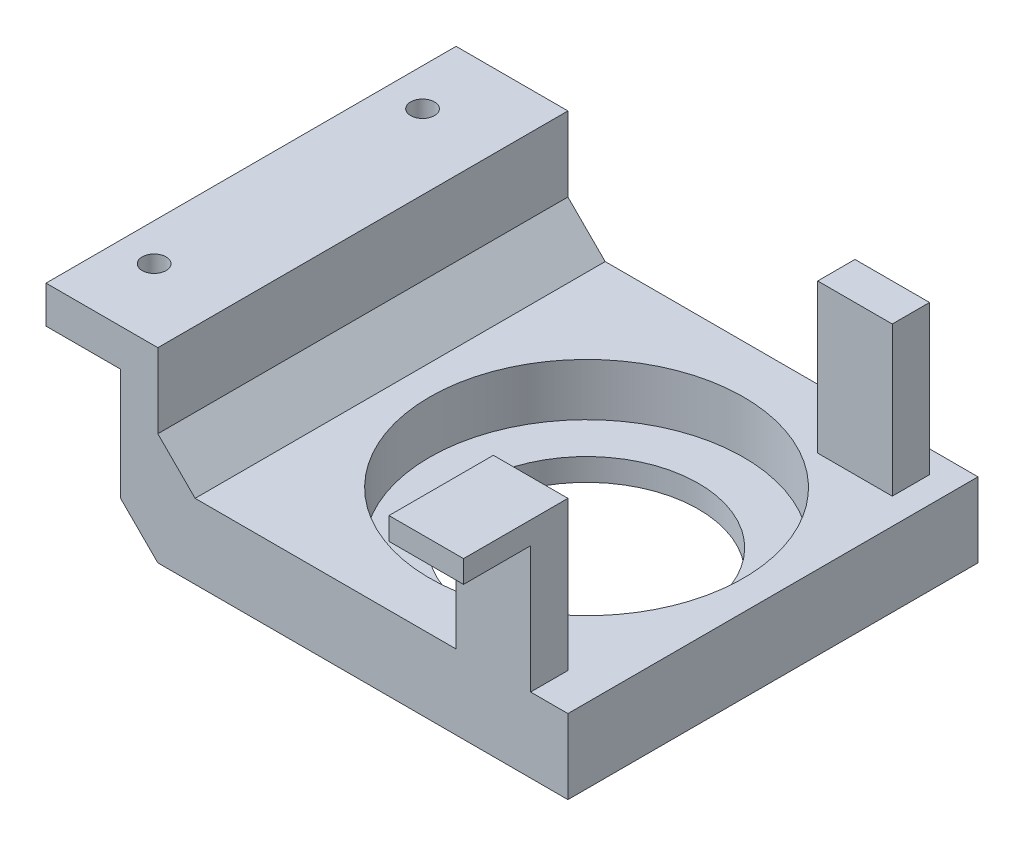
SolidWorks part; units mm, degrees
ref_plane "Alzado" through (0, 0, 0) normal (0, 0, 1) x (1, 0, 0)
ref_plane "Planta" through (0, 0, 0) normal (0, 1, 0) x (1, 0, 0)
ref_plane "Vista lateral" through (0, 0, 0) normal (1, 0, 0) x (0, 0, -1)
sketch "Croquis4" plane through (0, 0, 0) normal (0, 0, 1) x (1, 0, 0)
  line L0 (-31.4286, 5.7619) -> (-31.4286, 14.7619)
  line L5 (-26.4286, 4.7619) -> (28.5714, 4.7619)
  line L6 (-31.4286, 5.7619) -> (-31.4286, -5.2381)
  line L7 (-31.4286, -5.2381) -> (28.5714, -5.2381)
  line L8 (28.5714, 4.7619) -> (28.5714, -5.2381)
  line L9 (-31.4286, 5.7619) -> (28.5714, -5.2381) construction
  line L10 (-31.4286, -5.2381) -> (28.5714, 4.7619) construction
  line L11 (-31.4286, 14.7619) -> (-41.4286, 14.7619)
  line L12 (-41.4286, 14.7619) -> (-41.4286, 19.7619)
  line L13 (-41.4286, 19.7619) -> (-26.4286, 19.7619)
  line L14 (-26.4286, 19.7619) -> (-26.4286, 4.7619)
  point P0 (0, 0)
  dimension "D1" = 11
  dimension "D2" = 60
  dimension "D3" = 5
  dimension "D4" = 5
  dimension "D5" = 10
  dimension "D6" = 10
  dimension "D7" = 15
extrude "Saliente-Extruir2" add sketch "Croquis4" along normal blind 55
sketch "Croquis6" plane through (0, 4.7619, 0) normal (0, 1, 0) x (1, 0, 0)
  line L1 (28.5714, -55) -> (28.5714, 0) construction
  line L2 (28.5714, -27.5) -> (-26.4286, -27.5) construction
  line L3 (-26.4286, -55) -> (-26.4286, 0) construction
  circle A0 centre (3.5714, -27.5) radius 21.05
  dimension "D1" = 42.1
  dimension "D3" = 25
extrude "Cortar-Extruir1" cut sketch "Croquis6" against normal blind 7
sketch "Croquis8" plane through (0, -2.2381, 0) normal (0, 1, 0) x (1, 0, 0)
  circle A0 centre (3.5714, -27.5) radius 15
  dimension "D1" = 30
extrude "Cortar-Extruir2" cut sketch "Croquis8" against normal through all both and the other way through all
sketch "Croquis9" plane through (0, 14.7619, 0) normal (0, -1, 0) x (1, 0, 0)
  line L0 (-41.4286, 27.5) -> (-31.4286, 27.5) construction
  line L1 (-41.4286, 55) -> (-41.4286, 0) construction
  line L2 (-31.4286, 55) -> (-31.4286, 0) construction
  line L3 (-36.4286, 27.5) -> (-36.4286, 61.1151) construction
  circle A0 centre (-36.4286, 45.5) radius 1.6
  circle A2 centre (-36.4286, 9.5) radius 1.6
  dimension "D1" = 18
  dimension "D2" = 3.2
extrude "Cortar-Extruir3" cut sketch "Croquis9" against normal through all both and the other way through all
chamfer "Chaflán1" distance 5 angle 45 2 edges at (-26.4286, 4.7619, 27.5) (-31.4286, -5.2381, 27.5)
sketch "Croquis11" plane through (0, 4.7619, 0) normal (0, 1, 0) x (1, 0, 0)
  line L1 (28.5714, -55) -> (28.5714, 0) construction
  line L6 (28.5714, -27.5) -> (-21.4286, -27.5) construction
  line L7 (-21.4286, 0) -> (-21.4286, -55) construction
  line L12 (23.5714, -55) -> (23.5714, -50)
  line L13 (28.5714, -55) -> (-21.4286, -55) construction
  line L14 (23.5714, -50) -> (13.5714, -50)
  line L15 (13.5714, -50) -> (13.5714, -55)
  line L16 (13.5714, -55) -> (23.5714, -55)
  dimension "D1" = 10
  dimension "D2" = 5
  dimension "D3" = 5
extrude "Saliente-Extruir3" add sketch "Croquis11" along normal blind 20
sketch "Croquis12" plane through (0, 0, 55) normal (0, 0, 1) x (1, 0, 0)
  line L7 (13.5714, 24.7619) -> (13.5714, 21.7619)
  line L8 (13.5714, 24.7619) -> (23.5714, 24.7619) construction
  line L9 (13.5714, 24.7619) -> (13.5714, 4.7619) construction
  line L10 (13.5714, 21.7619) -> (23.5714, 21.7619)
  line L11 (23.5714, 24.7619) -> (23.5714, 4.7619) construction
  line L12 (23.5714, 21.7619) -> (23.5714, 24.7619)
  line L13 (23.5714, 24.7619) -> (13.5714, 24.7619)
  dimension "D1" = 3
extrude "Saliente-Extruir4" add sketch "Croquis12" along normal blind 9
sketch "Croquis13" plane through (0, 4.7619, 0) normal (0, 1, 0) x (1, 0, 0)
  line L0 (25.0714, -8) -> (25.0714, -3)
  line L1 (25.0714, -3) -> (15.0714, -3)
  line L2 (15.0714, -3) -> (15.0714, -8)
  line L3 (15.0714, -8) -> (25.0714, -8)
  line L4 (25.0714, -9) -> (25.0714, 2.2982) construction
  line L5 (25.0714, -9) -> (-6.9286, -9) construction
  dimension "D1" = 5
  dimension "D2" = 10
  dimension "D3" = 1
extrude "Saliente-Extruir5" add sketch "Croquis13" along normal blind 20
